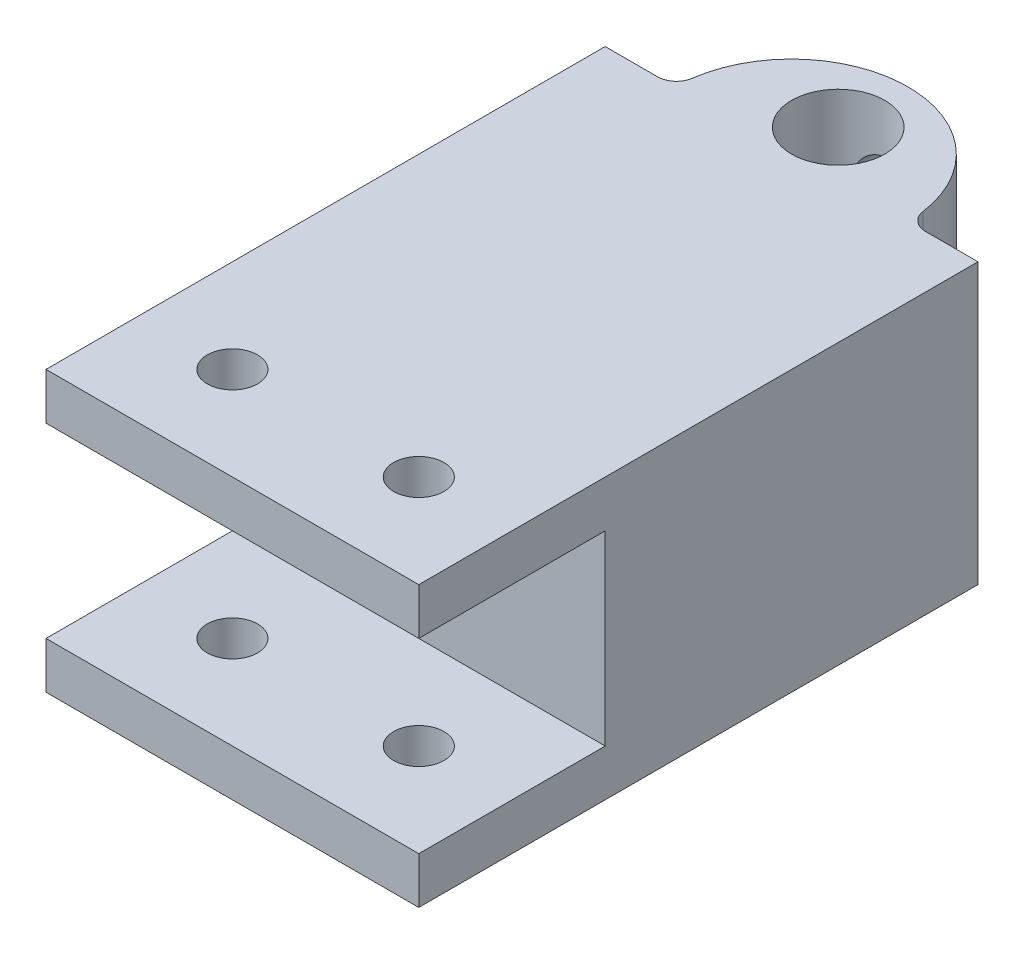
SolidWorks part; units mm, degrees
ref_plane "Front Plane" through (0, 0, 0) normal (0, 0, 1) x (1, 0, 0)
ref_plane "Top Plane" through (0, 0, 0) normal (0, 1, 0) x (1, 0, 0)
ref_plane "Right Plane" through (0, 0, 0) normal (1, 0, 0) x (0, 0, -1)
sketch "Sketch1" plane through (0, 0, 0) normal (0, 1, 0) x (1, 0, 0)
  line L0 (-15.875, 38.1) -> (-15.875, 61.9641) construction
  line L1 (-25.4, 38.1) -> (-15.875, 38.1)
  line L2 (-25.4, 38.1) -> (-25.4, -38.1)
  line L3 (-25.4, -38.1) -> (25.4, -38.1)
  line L4 (25.4, 38.1) -> (25.4, -38.1)
  line L5 (-25.4, 38.1) -> (25.4, -38.1) construction
  line L6 (-25.4, -38.1) -> (25.4, 38.1) construction
  line L7 (15.875, 38.1) -> (25.4, 38.1)
  circle A0 centre (0, 44.45) radius 6.35
  arc A1 (-15.875, 38.1) -> (15.875, 38.1) centre (0, 38.1) cw
  point P0 (0, 0)
  point P11 (0, 53.975)
  dimension "D3" = 12.7
  dimension "D1" = 76.2
  dimension "D2" = 50.8
  dimension "D4" = 31.75
extrude "Boss-Extrude1" add sketch "Sketch1" against normal blind 38.1
sketch "Sketch6" plane through (-25.4, 0, 0) normal (-1, 0, 0) x (0, 0, 1)
  line L0 (38.1, -38.1) -> (38.1, 0) construction
  line L1 (38.1, -31.75) -> (12.7, -31.75)
  line L2 (38.1, -31.75) -> (38.1, -6.35)
  line L3 (38.1, -6.35) -> (12.7, -6.35)
  line L4 (12.7, -31.75) -> (12.7, -6.35)
  line L5 (-38.1, -38.1) -> (38.1, -38.1) construction
  dimension "D1" = 6.35
  dimension "D2" = 25.4
extrude "Cut-Extrude3" cut sketch "Sketch6" against normal up to surface (50.8 mm away) up to face at (25.4, -19.05, 0)
sketch "Sketch7" plane through (0, -38.1, 0) normal (0, -1, 0) x (-1, 0, 0)
  line L0 (25.4, -25.4) -> (-25.4, -25.4) construction
  line L1 (25.4, 38.1) -> (25.4, -38.1) construction
  line L2 (-25.4, -38.1) -> (-25.4, 38.1) construction
  circle A0 centre (12.7, -25.4) radius 3.429
  circle A1 centre (-12.7, -25.4) radius 3.429
  dimension "D3" = 12.7
  dimension "D4" = 6.858
  dimension "D1" = 12.7
  dimension "D2" = 25.4
extrude "Cut-Extrude4" cut sketch "Sketch7" against normal through all
fillet "Fillet1" radius 2.54 2 edges at (15.875, -19.05, -38.1) (-15.875, -19.05, -38.1)
ref_plane "Plane1" through (0, 0, -88.9) normal (0, 0, 1) x (1, 0, 0)
sketch "Sketch10" plane through (0, 0, -88.9) normal (0, 0, 1) x (1, 0, 0)
  line L0 (15.7233, 0) -> (-15.7233, 0) construction
  line L1 (-15.7233, -38.1) -> (15.7233, -38.1) construction
  circle A0 centre (0, -27.94) radius 3.429
  circle A1 centre (0, -10.16) radius 3.429
  dimension "D1" = 10.16
  dimension "D2" = 6.858
  dimension "D3" = 10.16
extrude "Cut-Extrude5" cut sketch "Sketch10" along normal blind 47.752
